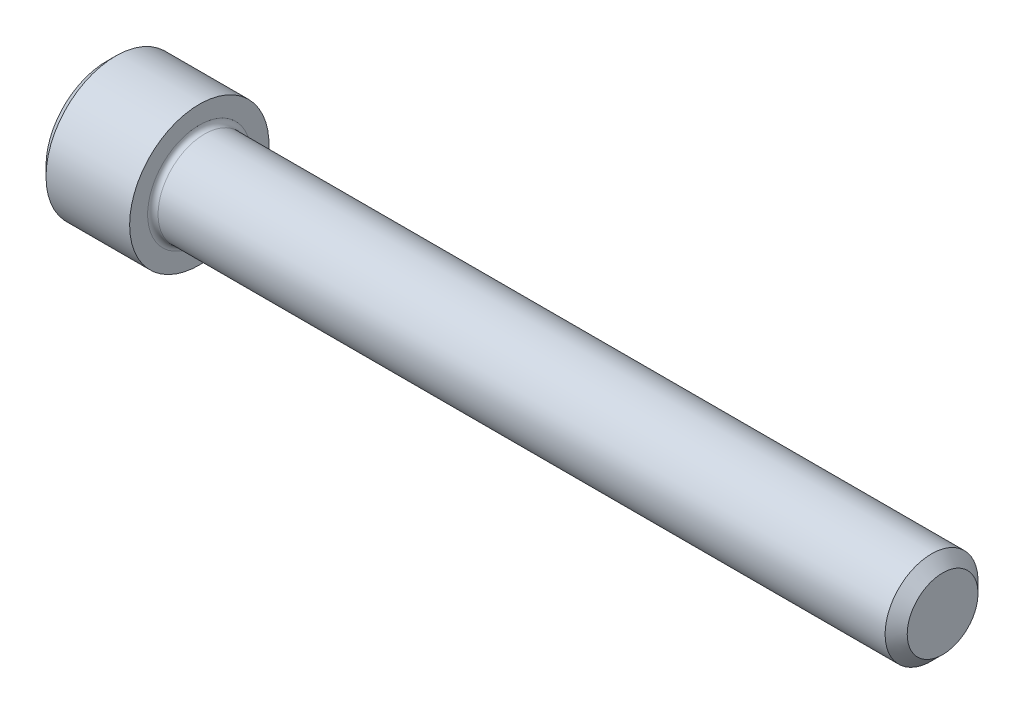
SolidWorks part; units mm, degrees
revolve "Base-Revolve" add sketch "BodySke"
sketch "BodySke" plane through (0, 0, 0) normal (0, 0, 1) x (1, 0, 0)
  line L0 (0, 0) -> (0, 4.1275)
  line L1 (0.635, 4.7625) -> (6.35, 4.7625)
  line L2 (6.35, 4.7625) -> (6.35, 3.175)
  line L3 (6.35, 3.175) -> (56.3943, 3.175)
  line L4 (57.15, 2.4193) -> (57.15, 0)
  line L5 (57.15, 0) -> (0, 0)
  line L6 (-31.75, 0) -> (127, 0) construction
  line L7 (0, 4.1275) -> (0.635, 4.7625)
  line L8 (57.15, 2.4193) -> (56.3943, 3.175)
  line L9 (0, -4.1275) -> (0.635, -4.7625) construction
  line L10 (57.15, -2.4193) -> (56.3943, -3.175) construction
  line L11 (7.62, 9.525) -> (7.62, 3.175) construction
  line L12 (31.75, 9.525) -> (31.75, 3.175) construction
  line L13 (19.05, 9.525) -> (19.05, 3.175) construction
  dimension "Diameter" = 6.35
  dimension "Head_ht" = 6.35
  dimension "Length" = 50.8
  dimension "Body_ch_ang" = 45
  dimension "Head_dia" = 9.525
  dimension "Head_ch_ang" = 45
  dimension "Head_side_ht" = 5.715
  dimension "Minor_dia" = 4.8387
  dimension "Advance" = 1.27
  dimension "Thread_nom" = 25.4
  dimension "Thread_length" = 38.1
cosmetic thread "ThreadCosmetic"
fillet "Fillet1" radius 0.3556 1 edges at (6.35, 0, 3.175)
ref_plane "Plane1" through (0, 0, 0) normal (0, 0, 1) x (1, 0, 0)
ref_plane "Plane2" through (0, 0, 0) normal (0, 1, 0) x (1, 0, 0)
ref_plane "Plane3" through (0, 0, 0) normal (1, 0, 0) x (0, 0, -1)
sketch "Sketch2" plane through (0, 0, 0) normal (0, 0, 1) x (1, 0, 0)
  line L0 (0, 2.3813) -> (3.048, 2.3812)
  line L1 (3.048, 2.3812) -> (4.4228, 0)
  line L2 (-31.75, 0) -> (127, 0) construction
  line L3 (4.4228, 0) -> (0, 0)
  line L4 (0, 0) -> (0, 2.3813)
  line L5 (0, 4.1275) -> (0, -4.1275) construction
  line L6 (0, 0) -> (47.625, 0) construction
  line L7 (6.35, -4.7625) -> (6.35, 4.7625) construction
  dimension "D1" = 2.3813
  dimension "D2" = 60
revolve "Hex-PreBroach" cut sketch "Sketch2" angle 360 about L6
sketch "Sketch3" plane through (0, 0, 0) normal (-1, 0, 0) x (0, 0.5, 0.866)
  line L0 (1.3748, 2.3813) -> (-1.3748, 2.3813)
  line L1 (-1.3748, 2.3813) -> (-2.7496, 0)
  line L2 (1.3748, 2.3813) -> (2.7496, 0)
  line L3 (1.3748, -2.3812) -> (2.7496, 0)
  line L4 (1.3748, -2.3812) -> (-1.3748, -2.3812)
  line L5 (-1.3748, -2.3812) -> (-2.7496, 0)
  dimension "D1" = 2.3813
  dimension "D2" = 2.3813
  dimension "Hex_size" = 4.7625
extrude "Hex" cut sketch "Sketch3" against normal blind 3.048
sketch "Sketch4" plane through (0, 0, 0) normal (-1, 0, 0) x (0, 0, 1)
  line L0 (0, 0) -> (2.8067, 0)
  line L1 (0, 0) -> (6.1484, 3.5498) construction
  line L2 (0, 0) -> (1.4033, 2.4307)
  line L3 (2.3336, 0.614) -> (2.6851, 0.817)
  line L4 (1.6986, 1.7139) -> (2.0501, 1.9169)
  arc A0 (2.3336, 0.614) -> (1.6986, 1.7139) centre (0, 0) ccw
  arc A1 (2.8067, 0) -> (2.6851, 0.817) centre (0, 0) ccw
  arc A2 (1.4033, 2.4307) -> (2.0501, 1.9169) centre (0, 0) cw
  dimension "D1" = 30
  dimension "D2" = 60
  dimension "Spline_p_dim" = 1.27
  dimension "D3" = 0.635
extrude "Spline" [suppressed] cut sketch "Sketch4" against normal blind 3.048
pattern_circular "CirPattern1" [suppressed] count 6 every 60
sketch "Sketch5" plane through (0, 0, 0) normal (0, 0, 1) x (1, 0, 0)
  line L0 (-31.75, 0) -> (127, 0) construction
  line L2 (0, 4.1275) -> (0, -4.1275) construction
  circle A0 centre (2.159, 0) radius 0.5905
  dimension "Drilled_hole_dia" = 1.1811
  dimension "Drilled_hole_loc" = 2.159
extrude "Hole" [suppressed] cut sketch "Sketch5" against normal through all and the other way through all
pattern_circular "Drilled-4" [suppressed] count 2 every 60
pattern_circular "Drilled-6" [suppressed] count 3 every 60
sketch "ThdSchSke" plane through (0, 0, 0) normal (0, 0, 1) x (1, 0, 0)
  line L0 (31.75, -2.4193) -> (31.2209, -3.175)
  line L1 (31.75, -2.4193) -> (32.2791, -3.175)
  line L2 (32.2791, -3.175) -> (32.2791, -3.9687)
  line L3 (-3.175, 0) -> (5.1513, 0) construction
  line L5 (32.2791, -3.9687) -> (31.2209, -3.9687)
  line L6 (31.2209, -3.9687) -> (31.2209, -3.175)
  line L7 (0, 4.1275) -> (0, -4.1275) construction
  dimension "Thread_minor" = 4.8387
  dimension "Diameter" = 6.35
revolve "ThreadSchematic" [suppressed] cut sketch "ThdSchSke" angle 360 about L3
pattern_linear "ThdSchPat" [suppressed]
equation "\"D2@Sketch3\" = \"Hex_size@Sketch3\" / 2"
equation "\"D1@Sketch3\" = \"Hex_size@Sketch3\" / 2"
equation "\"D1@Sketch2\" = \"Hex_size@Sketch3\" / 2"
equation "\"D3@Sketch4\" = \"Spline_p_dim@Sketch4\" / 2"
equation "\"Thread_minor@ThreadCosmetic\"  =  \"Minor_dia@BodySke\""
equation "\"D2@CirPattern1\" = 360 / \"Num_teeth@CirPattern1\""
equation "\"Wall_thickness@Sketch2\" = \"Head_ht@BodySke\" - \"Key_eng@Hex\""
equation "\"Thread_length@ThreadCosmetic\" = ((sgn( (\"Length@BodySke\" - \"Advance@BodySke\" ) - \"Thread_nom@BodySke\" )-1)*( (\"Length@BodySke\" - \"Advance@BodySke\" ) - \"Thread_nom@BodySke\" ))/-2+ \"Thread_nom@BodySke\""
equation "\"Thread_minor@ThdSchSke\" = \"Minor_dia@BodySke\""
equation "\"Diameter@ThdSchSke\" = \"Diameter@BodySke\""
equation "\"Overcut@ThdSchSke\" = \"Diameter@BodySke\" * 1.25"
equation "\"Start@ThdSchSke\" = \"Head_ht@BodySke\" + \"Length@BodySke\" - \"Thread_length@ThreadCosmetic\"  '---Non-countersunk---"
equation "\"Num_threads@ThdSchPat\" = int( \"Thread_length@ThreadCosmetic\" / \"Advance@BodySke\" + 0.999 )  + 1"
equation "\"Advance@ThdSchPat\" = \"Thread_length@ThreadCosmetic\" /  (\"Num_threads@ThdSchPat\" - 1) 'relax it"
equation "\"Num_threads@ThdSchPat\" = \"Num_threads@ThdSchPat\" - sgn( \"Num_threads@ThdSchPat\" - 1) '---chamfered tips only---"
